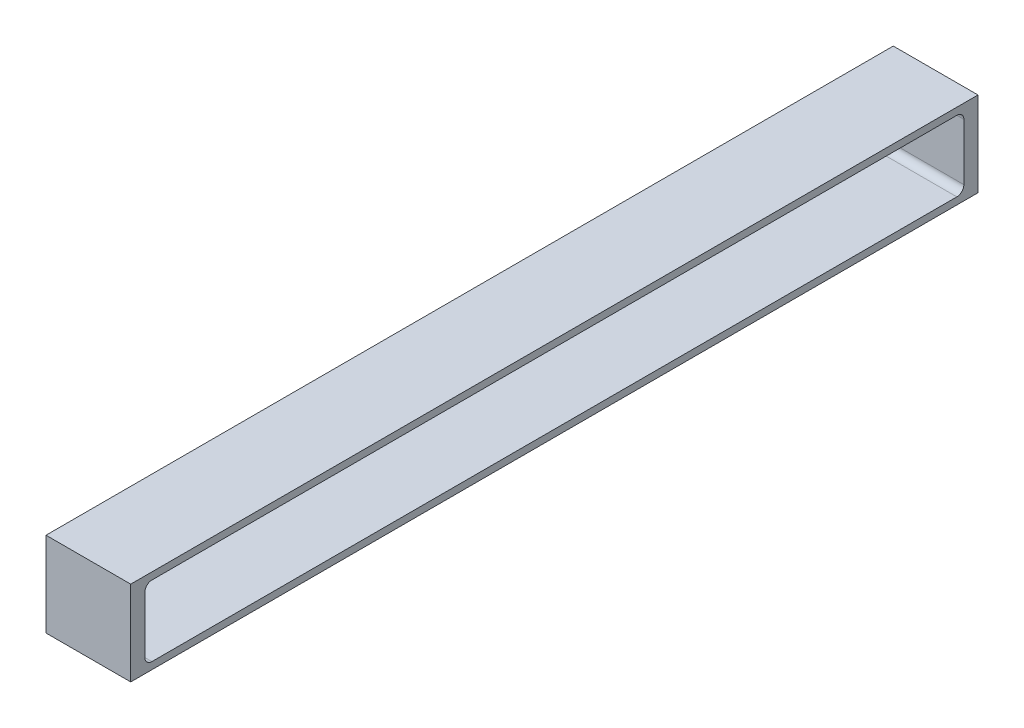
SolidWorks part; units mm, degrees
ref_plane "Front Plane" through (0, 0, 0) normal (0, 0, 1) x (1, 0, 0)
ref_plane "Top Plane" through (0, 0, 0) normal (0, 1, 0) x (1, 0, 0)
ref_plane "Right Plane" through (0, 0, 0) normal (1, 0, 0) x (0, 0, -1)
sketch "Sketch2" plane through (0, 0, 0) normal (0, 0, 1) x (1, 0, 0)
  line L1 (0, 0) -> (38.1, 0)
  line L2 (0, 0) -> (0, 38.1)
  line L3 (0, 38.1) -> (38.1, 38.1)
  line L4 (38.1, 0) -> (38.1, 38.1)
  dimension "D1" = 38.1
extrude "Boss-Extrude1" add sketch "Sketch2" along normal blind 381
sketch "Sketch3" plane through (38.1, 0, 0) normal (1, 0, 0) x (0, 0, -1)
  line L4 (-190.5, 34.925) -> (-190.5, 38.1) construction
  line L5 (-374.65, 34.925) -> (-6.35, 34.925)
  line L6 (-374.65, 34.925) -> (-374.65, 3.175)
  line L7 (-374.65, 3.175) -> (-6.35, 3.175)
  line L8 (-6.35, 34.925) -> (-6.35, 3.175)
  line L9 (-381, 38.1) -> (0, 38.1) construction
  line L10 (-6.35, 19.05) -> (0, 19.05) construction
  line L11 (0, 0) -> (0, 38.1) construction
  dimension "D1" = 6.35
  dimension "D2" = 3.175
extrude "Cut-Extrude1" cut sketch "Sketch3" against normal offset from surface (33.3375 mm away) 4.7625 up to face at (0, 19.05, 190.5)
fillet "Fillet1" radius 3.175 4 edges at (21.4313, 3.175, 6.35) (21.4313, 3.175, 374.65) (21.4313, 34.925, 374.65) (21.4313, 34.925, 6.35)
